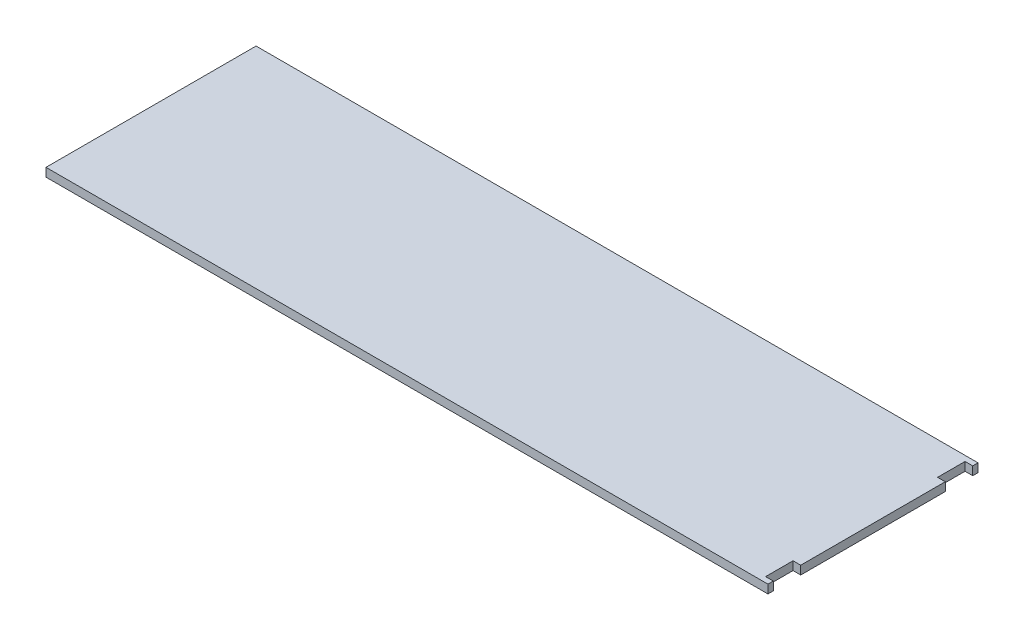
SolidWorks part; units mm, degrees
ref_plane "Front Plane" through (0, 0, 0) normal (0, 0, 1) x (1, 0, 0)
ref_plane "Top Plane" through (0, 0, 0) normal (0, 1, 0) x (1, 0, 0)
ref_plane "Right Plane" through (0, 0, 0) normal (1, 0, 0) x (0, 0, -1)
sketch "Sketch1" plane through (0, 0, 0) normal (0, 1, 0) x (1, 0, 0)
  line L1 (-72.0936, 291.3988) -> (1002.6439, 291.3988)
  line L2 (-72.0936, 291.3988) -> (-72.0936, -21.3387)
  line L3 (-72.0936, -21.3387) -> (1002.6439, -21.3387)
  line L4 (1002.6439, 291.3988) -> (1002.6439, -21.3387)
  dimension "D1" = 1074.7375
  dimension "D2" = 312.7375
extrude "Boss-Extrude1" add sketch "Sketch1" along normal blind 12.7
sketch "Sketch2" plane through (0, 12.7, 0) normal (0, 1, 0) x (1, 0, 0)
  line L0 (991.2139, 283.5502) -> (991.2139, 242.6562)
  line L1 (1002.6439, 283.5502) -> (991.2139, 283.5502)
  line L2 (991.2139, 242.6562) -> (1002.6439, 242.6562)
  line L5 (1002.3264, 253.7687) -> (1002.6439, 253.7687)
  line L7 (991.2139, 27.4928) -> (1002.6439, 27.4928)
  line L8 (1002.6439, -21.3387) -> (1002.6439, 291.3988)
  line L9 (1002.6439, 291.3988) -> (-72.0936, 291.3988)
  line L10 (-72.0936, 291.3988) -> (-72.0936, -21.3387)
  line L11 (-72.0936, -21.3387) -> (1002.6439, -21.3387)
  line L12 (1002.6439, -21.3387) -> (1002.6439, 291.3988)
  line L13 (1002.6439, 291.3988) -> (-72.0936, 291.3988)
  line L14 (-72.0936, 291.3988) -> (-72.0936, -21.3387)
  line L15 (-72.0936, -21.3387) -> (1002.6439, -21.3387)
  line L17 (991.2139, -13.4012) -> (991.2139, 27.4928)
  line L18 (991.2139, -13.4012) -> (1002.6439, -13.4012)
  dimension "D2" = 11.43
  dimension "D3" = 7.9375
  dimension "D4" = 40.894
  dimension "D1" = 0
extrude "Cut-Extrude2" cut sketch "Sketch2" against normal through all
